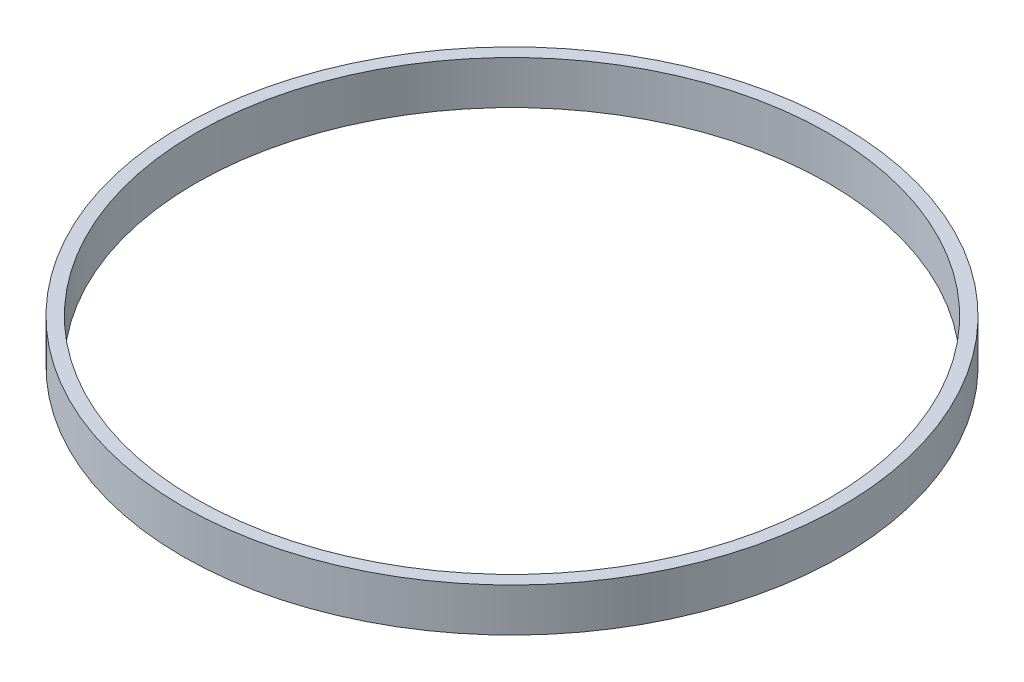
SolidWorks part; units mm, degrees
ref_plane "Alzado" through (0, 0, 0) normal (0, 0, 1) x (1, 0, 0)
ref_plane "Planta" through (0, 0, 0) normal (0, 1, 0) x (1, 0, 0)
ref_plane "Vista lateral" through (0, 0, 0) normal (1, 0, 0) x (0, 0, -1)
sketch "Croquis1" plane through (0, 0, 0) normal (0, 1, 0) x (1, 0, 0)
  line L0 (-51.6188, 51.6188) -> (-51.6188, -51.6188) construction
  line L1 (-51.6188, -51.6188) -> (-51.5202, -51.7754) construction
  line L2 (-51.6188, 51.6188) -> (51.6188, 51.6188) construction
  line L3 (51.6188, 51.6188) -> (51.6188, -51.6188) construction
  line L4 (-51.5202, -51.7754) -> (51.6188, -51.6188) construction
  line L5 (-51.6188, 51.6188) -> (51.6188, -51.6188) construction
  line L6 (-51.5202, -51.7754) -> (51.6188, 51.6188) construction
  line L7 (-73, 0) -> (73, 0) construction
  circle A0 centre (0, 0) radius 73
  circle A1 centre (0, 0) radius 76
  point P10 (0, 0)
  point P13 (0, 0)
  dimension "D1" = 146
  dimension "D2" = 3
extrude "Saliente-Extruir1" add sketch "Croquis1" along normal blind 10
